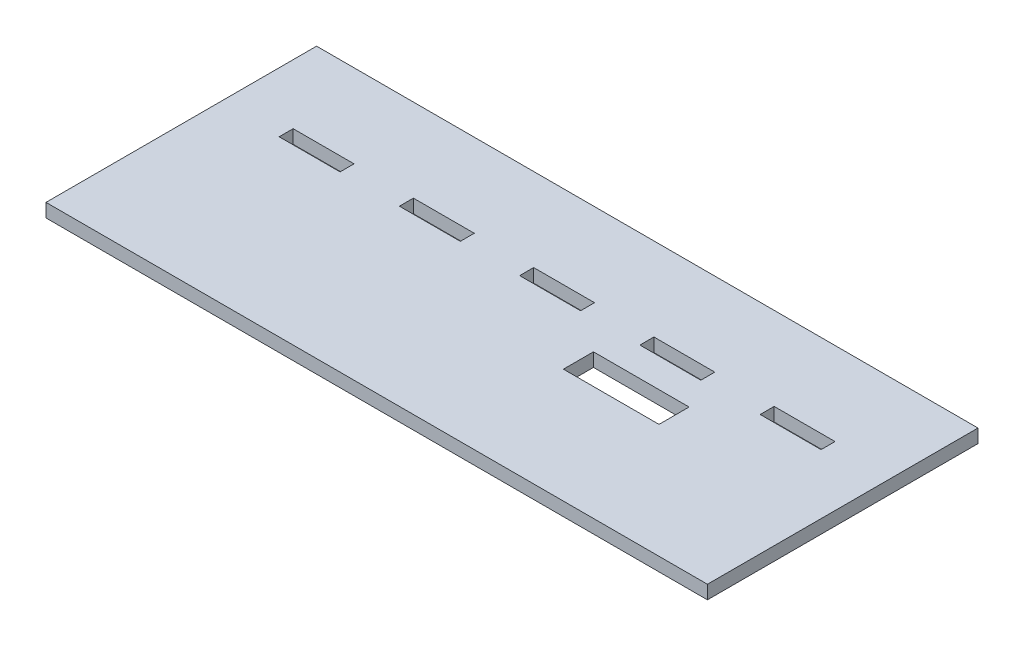
SolidWorks part; units mm, degrees
ref_plane "Front Plane" through (0, 0, 0) normal (0, 0, 1) x (1, 0, 0)
ref_plane "Top Plane" through (0, 0, 0) normal (0, 1, 0) x (1, 0, 0)
ref_plane "Right Plane" through (0, 0, 0) normal (1, 0, 0) x (0, 0, -1)
sketch "Sketch2" plane through (0, 0, 0) normal (0, 1, 0) x (1, 0, 0)
  line L3 (110, 45) -> (-110, 45)
  line L4 (110, 45) -> (110, -45)
  line L5 (110, -45) -> (-110, -45)
  line L6 (-110, 45) -> (-110, -45)
  line L7 (110, 45) -> (-110, -45) construction
  line L8 (110, -45) -> (-110, 45) construction
  point P0 (0, 0)
  dimension "D1" = 220
  dimension "D2" = 90
extrude "Boss-Extrude1" add sketch "Sketch2" along normal blind 4.5
sketch "Sketch3" plane through (0, 0, 0) normal (0, -1, 0) x (1, 0, 0)
  line L0 (0, 0) -> (0, -15) construction
  line L1 (50.125, -12.675) -> (50.125, -17.325)
  line L2 (10.125, -12.675) -> (-10.125, -12.675)
  line L3 (10.125, -12.675) -> (10.125, -17.325)
  line L4 (10.125, -17.325) -> (-10.125, -17.325)
  line L5 (-10.125, -12.675) -> (-10.125, -17.325)
  line L6 (10.125, -12.675) -> (-10.125, -17.325) construction
  line L7 (10.125, -17.325) -> (-10.125, -12.675) construction
  line L8 (50.125, -12.675) -> (29.875, -12.675)
  line L9 (29.875, -12.675) -> (29.875, -17.325)
  line L10 (50.125, -17.325) -> (29.875, -17.325)
  line L11 (90.125, -12.675) -> (90.125, -17.325)
  line L12 (90.125, -12.675) -> (69.875, -12.675)
  line L13 (69.875, -12.675) -> (69.875, -17.325)
  line L14 (90.125, -17.325) -> (69.875, -17.325)
  line L15 (10.125, -12.675) -> (50.125, -12.675) construction
  line L16 (-90.125, -17.325) -> (-69.875, -17.325)
  line L17 (-69.875, -12.675) -> (-69.875, -17.325)
  line L18 (-90.125, -12.675) -> (-69.875, -12.675)
  line L19 (-90.125, -12.675) -> (-90.125, -17.325)
  line L20 (-50.125, -17.325) -> (-29.875, -17.325)
  line L21 (-29.875, -12.675) -> (-29.875, -17.325)
  line L22 (-50.125, -12.675) -> (-29.875, -12.675)
  line L23 (-50.125, -12.675) -> (-50.125, -17.325)
  dimension "D1" = 15
  dimension "D2" = 20.25
  dimension "D3" = 4.65
  dimension "D5" = 40
  dimension "D4" = 3
extrude "Cut-Extrude1" cut sketch "Sketch3" against normal through all
sketch "Sketch4" plane through (0, 0, 0) normal (0, -1, 0) x (1, 0, 0)
  line L0 (0, 2) -> (40, 2) construction
  line L1 (0, 0) -> (0, 2) construction
  line L2 (55.9014, 7) -> (24.0986, 7)
  line L3 (55.9014, 7) -> (55.9014, -3)
  line L4 (55.9014, -3) -> (24.0986, -3)
  line L5 (24.0986, 7) -> (24.0986, -3)
  line L6 (55.9014, 7) -> (24.0986, -3) construction
  line L7 (55.9014, -3) -> (24.0986, 7) construction
  point P7 (0, 0)
  dimension "D1" = 40
  dimension "D2" = 10
  dimension "D3" = 2
extrude "Input link cut" cut sketch "Sketch4" against normal through all
